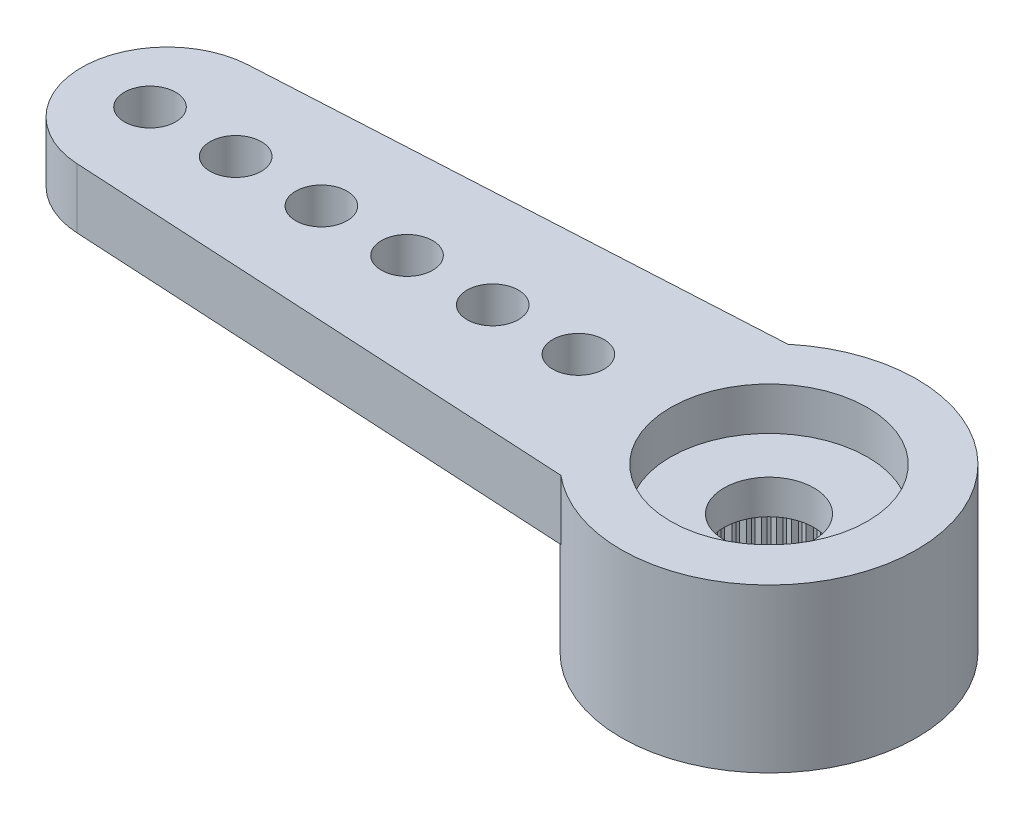
SolidWorks part; units mm, degrees
material "PVC Rígido"
ref_plane "Plano frontal" through (0, 0, 0) normal (0, 0, 1) x (1, 0, 0)
ref_plane "Plano superior" through (0, 0, 0) normal (0, 1, 0) x (1, 0, 0)
ref_plane "Plano direito" through (0, 0, 0) normal (1, 0, 0) x (0, 0, -1)
sketch "Esboço1" plane through (0, 0, 0) normal (0, 1, 0) x (1, 0, 0)
  line L0 (0, 0) -> (-14.05, 0) construction
  line L1 (-14.1591, 1.997) -> (-2.2091, 2.65)
  line L2 (-2.2091, -2.65) -> (-14.1591, -1.997)
  arc A0 (-2.2091, -2.65) -> (-2.2091, 2.65) centre (0, 0) ccw
  arc A1 (-14.1591, 1.997) -> (-14.1591, -1.997) centre (-14.05, 0) ccw
  dimension "D1" = 6.9
  dimension "D2" = 4
  dimension "D3" = 19.5
  dimension "D4" = 5.3
extrude "Ressalto-extrusão1" add sketch "Esboço1" against normal blind 1.4
sketch "Esboço2" plane through (0, -1.4, 0) normal (0, -1, 0) x (1, 0, 0)
  arc A0 (-2.2091, -2.65) -> (-2.2091, 2.65) centre (0, 0) ccw construction
  circle A1 centre (0, 0) radius 3.45
extrude "Ressalto-extrusão2" add sketch "Esboço2" along normal offset from surface (2.4 mm away) 3.8 up to face at (-7.242, 0, 0)
hole_wizard "Furo4" positions "Esboço9" profile "Esboço10" legacy end condition through all
sketch "Esboço9" plane through (0, 0, 0) normal (0, 1, 0) x (1, 0, 0)
  line L1 (-14.45, 0) -> (0, 0) construction
  arc A2 (-14.1591, 1.997) -> (-14.1591, -1.997) centre (-14.05, 0) ccw construction
  point P0 (-14.45, 0)
  point P19 (-16.05, 0)
  dimension "D1" = 1.6
sketch "Esboço10" plane through (-14.45, 0, 0) normal (1, 0, 0) x (0, 0, 1)
  line L0 (0, 0) -> (0, 3.8)
  line L1 (0, 3.8) -> (0.6, 3.8)
  line L2 (0.6, 3.8) -> (0.6, 0)
  line L3 (0.6, 0) -> (0, 0)
  line L4 (0, 110) -> (0, -10) construction
  dimension "Diameter" = 1.2
  dimension "Depth" = 3.8
pattern_linear "Padrão linear1" count 6 spacing 2 along (1, 0, 0) of "Furo4"
hole_wizard "Furo1" positions "Esboço3" profile "Esboço4" legacy
sketch "Esboço3" plane through (0, -3.8, 0) normal (0, -1, 0) x (-1, 0, 0)
  point P0 (0, 0)
sketch "Esboço4" plane through (0, -3.8, 0) normal (1, 0, 0) x (0, 0, -1)
  line L0 (0, 0) -> (0, 2)
  line L1 (0, 2) -> (2.475, 2)
  line L2 (2.475, 2) -> (2.475, 0)
  line L3 (2.475, 0) -> (0, 0)
  line L4 (0, 110) -> (0, -10) construction
  dimension "Diameter" = 4.95
  dimension "Depth" = 2
hole_wizard "Furo2" positions "Esboço5" profile "Esboço6" legacy
sketch "Esboço5" plane through (0, 0, 0) normal (0, 1, 0) x (1, 0, 0)
  point P0 (0, 0)
sketch "Esboço6" plane through (0, 0, 0) normal (1, 0, 0) x (0, 0, 1)
  line L0 (0, 0) -> (0, 1)
  line L1 (0, 1) -> (2.3, 1)
  line L2 (2.3, 1) -> (2.3, 0)
  line L3 (2.3, 0) -> (0, 0)
  line L4 (0, 110) -> (0, -10) construction
  dimension "Diameter" = 4.6
  dimension "Depth" = 1
hole_wizard "Furo3" positions "Esboço7" profile "Esboço8" legacy end condition through all
sketch "Esboço7" plane through (0, 0, 0) normal (0, 1, 0) x (1, 0, 0)
  point P0 (0, 0)
sketch "Esboço8" plane through (0, 0, 0) normal (1, 0, 0) x (0, 0, 1)
  line L0 (0, 0) -> (0, 3.8)
  line L1 (0, 3.8) -> (1.05, 3.8)
  line L2 (1.05, 3.8) -> (1.05, 0)
  line L3 (1.05, 0) -> (0, 0)
  line L4 (0, 110) -> (0, -10) construction
  dimension "Diameter" = 2.1
  dimension "Depth" = 3.8
sketch "Esboço11" plane through (0, -3.8, 0) normal (0, -1, 0) x (1, 0, 0)
  line L0 (-0.0981, 2.4731) -> (0, 2.375)
  line L1 (0, 2.375) -> (0.0981, 2.4731)
  line L2 (0, 0) -> (0, 2.475) construction
  circle A0 centre (0, 0) radius 2.375 construction
  circle A1 centre (0, 0) radius 2.475
  arc A2 (0.0981, 2.4731) -> (-0.0981, 2.4731) centre (0, 0) ccw
  dimension "D3" = 4.75
  dimension "D2" = 0.1
  dimension "D1" = 0
extrude "Ressalto-extrusão3" add sketch "Esboço11" against normal up to surface (2 mm away) up to face at (0, -1.8, 1.05)
pattern_circular "PadrãoCircular1" count 60 over 360 about axis through (0, 0, 0) along (0, 1, 0) of "Ressalto-extrusão3"
sketch "Sketch1" plane through (0, 0, 0) normal (0, 1, 0) x (1, 0, 0)
  circle A0 centre (-14.45, 0) radius 0.6
